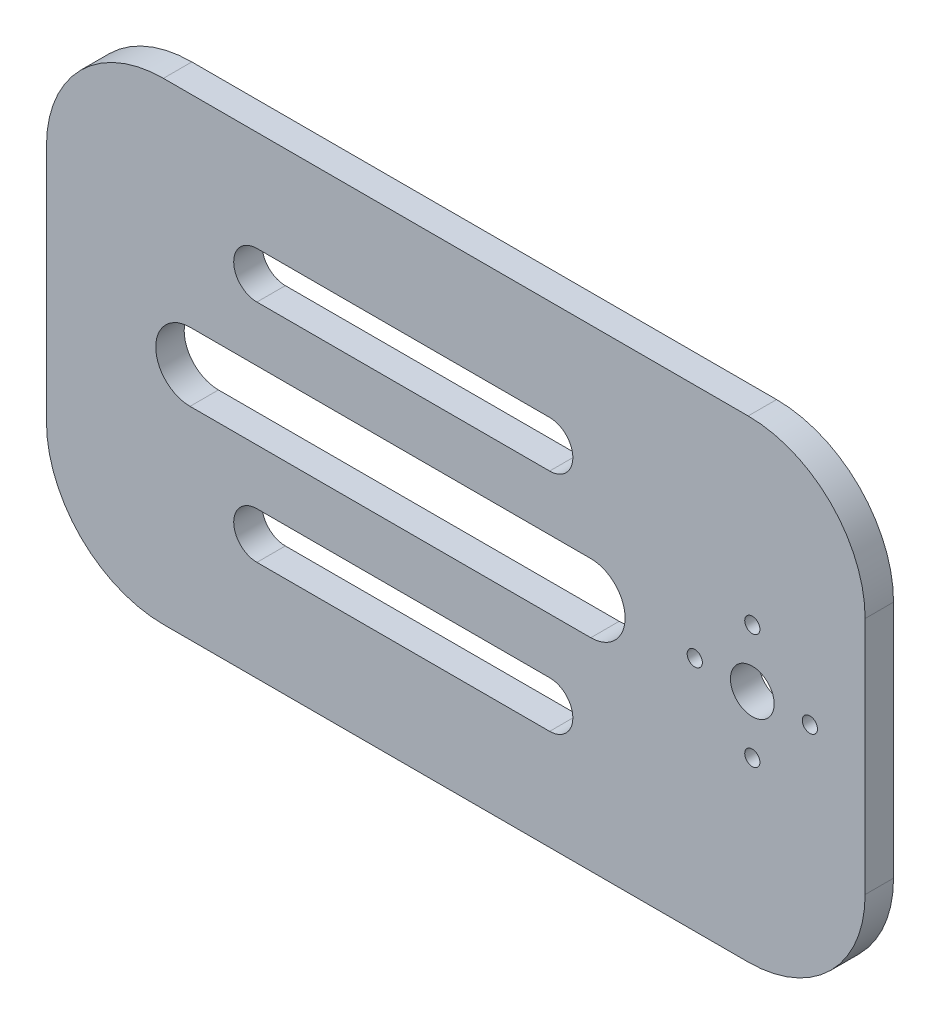
SolidWorks part; units mm, degrees
material "5052-O"
ref_plane "Front Plane" through (0, 0, 0) normal (0, 0, 1) x (1, 0, 0)
ref_plane "Top Plane" through (0, 0, 0) normal (0, 1, 0) x (1, 0, 0)
ref_plane "Right Plane" through (0, 0, 0) normal (1, 0, 0) x (0, 0, -1)
sketch "Sketch1" plane through (0, 0, 0) normal (0, 0, 1) x (1, 0, 0)
  line L0 (24.5, 0) -> (-153.3, 0) construction
  line L1 (-0.9, -51.3588) -> (-127.9, -51.3588)
  line L2 (24.5, -25.9588) -> (24.5, 25.9588)
  line L3 (-0.9, 51.3588) -> (-127.9, 51.3588)
  line L4 (-153.3, -25.9588) -> (-153.3, 25.9588)
  circle A0 centre (0, 0) radius 24.5 construction
  circle A1 centre (12.5, 0) radius 1.65 construction
  circle A2 centre (0, -12.5) radius 1.65 construction
  circle A4 centre (-12.5, 0) radius 1.65 construction
  circle A5 centre (0, 12.5) radius 1.65 construction
  circle A6 centre (12.5, 0) radius 1.65
  circle A7 centre (0, -12.5) radius 1.65
  circle A8 centre (0, 0) radius 4.75 construction
  circle A9 centre (-12.5, 0) radius 1.65
  circle A10 centre (0, 12.5) radius 1.65
  circle A11 centre (0, 0) radius 4.75
  arc A12 (-0.9, -51.3588) -> (24.5, -25.9588) centre (-0.9, -25.9588) ccw
  arc A13 (24.5, 25.9588) -> (-0.9, 51.3588) centre (-0.9, 25.9588) ccw
  arc A14 (-127.9, 51.3588) -> (-153.3, 25.9588) centre (-127.9, 25.9588) ccw
  arc A15 (-127.9, -51.3588) -> (-153.3, -25.9588) centre (-127.9, -25.9588) cw
  point P26 (24.5, -51.3588)
  point P29 (24.5, 51.3588)
  dimension "D3" = 25.4
  dimension "D1" = 102.7176
  dimension "D2" = 177.8
extrude "Boss-Extrude1" add sketch "Sketch1" along normal blind 6.1722
sketch "Sketch2" plane through (0, 0, 0) normal (0, 0, -1) x (-1, 0, 0)
  line L0 (44.0193, 24.4792) -> (107.5916, 24.4792) construction
  line L1 (44.0193, 29.5211) -> (107.5916, 29.5211)
  line L2 (44.0193, 19.4374) -> (107.5916, 19.4374)
  line L3 (44.0193, -24.4793) -> (107.5916, -24.4793) construction
  line L4 (44.0193, -19.4374) -> (107.5916, -19.4374)
  line L5 (44.0193, -29.5212) -> (107.5916, -29.5212)
  line L6 (35.0805, 0) -> (122.1184, 0) construction
  line L7 (35.0805, 7.4422) -> (122.1184, 7.4422)
  line L8 (35.0805, -7.4422) -> (122.1184, -7.4422)
  line L9 (72.2856, -24.4793) -> (72.2856, 24.4793) construction
  line L10 (112.6335, -24.4793) -> (112.6335, 24.4792) construction
  line L11 (91.4606, -24.4793) -> (91.4606, 24.4792) construction
  line L12 (74.5335, -24.4793) -> (74.5335, 24.4792) construction
  line L13 (129.5606, -24.4793) -> (129.5606, 24.4792) construction
  line L14 (112.6335, 24.4792) -> (129.5606, 24.4792) construction
  line L15 (74.5335, 11.1748) -> (91.4606, 11.1748) construction
  line L16 (129.5606, -24.4793) -> (107.5916, -24.4793) construction
  circle A0 centre (44.0193, 24.4792) radius 5.0419 construction
  circle A1 centre (44.0193, -24.4793) radius 5.0419 construction
  circle A2 centre (58.1525, 0) radius 7.4422 construction
  circle A3 centre (44.0193, 24.4792) radius 5.0419 construction
  circle A4 centre (44.0193, -24.4793) radius 5.0419 construction
  circle A5 centre (58.1525, 0) radius 7.4422 construction
  arc A6 (44.0193, 29.5211) -> (44.0193, 19.4374) centre (44.0193, 24.4792) ccw
  arc A7 (107.5916, 19.4374) -> (107.5916, 29.5211) centre (107.5916, 24.4792) ccw
  arc A8 (44.0193, -19.4374) -> (44.0193, -29.5212) centre (44.0193, -24.4793) ccw
  arc A9 (107.5916, -29.5212) -> (107.5916, -19.4374) centre (107.5916, -24.4793) ccw
  arc A10 (35.0805, 7.4422) -> (35.0805, -7.4422) centre (35.0805, 0) ccw
  arc A11 (122.1184, -7.4422) -> (122.1184, 7.4422) centre (122.1184, 0) ccw
  circle A13 centre (29.8862, 0) radius 2.2479 construction
  circle A14 centre (29.8862, 0) radius 2.2479 construction
  circle A16 centre (72.2856, -24.4793) radius 2.2479 construction
  circle A17 centre (72.2856, 24.4793) radius 2.2479 construction
  circle A18 centre (86.4187, 0) radius 5.0419 construction
  circle A19 centre (86.4187, 0) radius 5.0419 construction
  point P9 (75.8054, 24.4792)
  point P15 (75.8054, -24.4793)
  point P21 (78.5995, 0)
  dimension "D1" = 38.1
extrude "Cut-Extrude1" cut sketch "Sketch2" against normal through all
